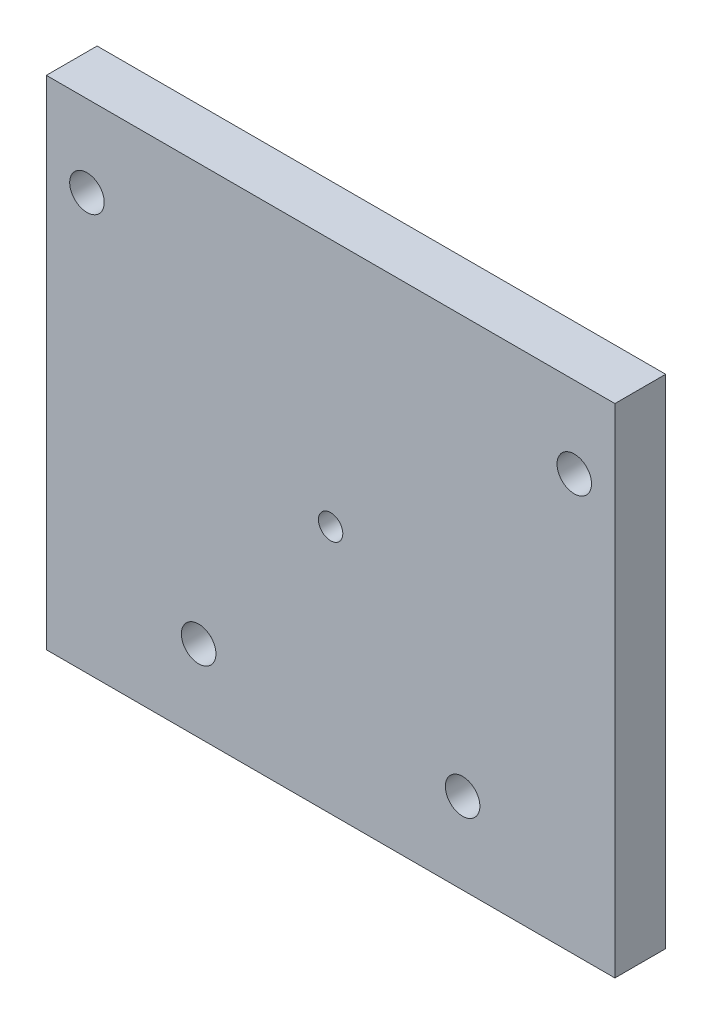
SolidWorks part; units mm, degrees
ref_plane "Front Plane" through (0, 0, 0) normal (0, 0, 1) x (1, 0, 0)
ref_plane "Top Plane" through (0, 0, 0) normal (0, 1, 0) x (1, 0, 0)
ref_plane "Right Plane" through (0, 0, 0) normal (1, 0, 0) x (0, 0, -1)
sketch "Sketch1" plane through (0, 0, 0) normal (0, 0, 1) x (1, 0, 0)
  line L2 (-140, -122.5) -> (-140, 122.5)
  line L3 (-140, 122.5) -> (140, 122.5)
  line L4 (140, -122.5) -> (140, 122.5)
  line L5 (-140, -122.5) -> (140, -122.5)
  circle A6 centre (-120, 82.5) radius 5.25
  circle A7 centre (120, 82.5) radius 5.25
  circle A8 centre (-65, -82.5) radius 5.25
  circle A9 centre (65, -82.5) radius 5.25
  circle A10 centre (0, 0) radius 6
  point P0 (0, 0)
  dimension "D1" = 2
  dimension "D2" = 2
extrude "Boss-Extrude1" add sketch "Sketch1" along normal blind 25
sketch "Sketch2" plane through (0, 0, 25) normal (0, 0, 1) x (1, 0, 0)
  circle A0 centre (-120, 82.5) radius 8.5
  circle A1 centre (120, 82.5) radius 8.5
  circle A2 centre (65, -82.5) radius 8.5
  circle A3 centre (-65, -82.5) radius 8.5
extrude "Cut-Extrude1" cut sketch "Sketch2" against normal blind 12
